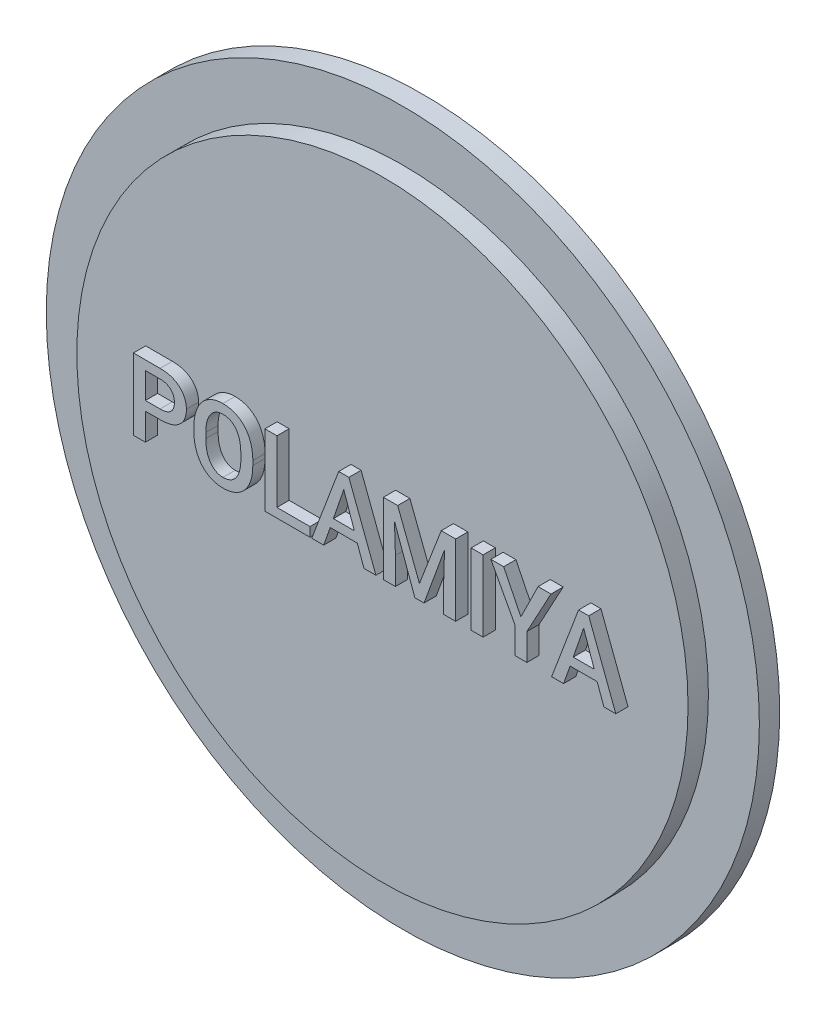
SolidWorks part; units mm, degrees
ref_plane "前视基准面" through (0, 0, 0) normal (0, 0, 1) x (1, 0, 0)
ref_plane "上视基准面" through (0, 0, 0) normal (0, 1, 0) x (1, 0, 0)
ref_plane "右视基准面" through (0, 0, 0) normal (1, 0, 0) x (0, 0, -1)
sketch "草图1" plane through (0, 0, 0) normal (0, 0, 1) x (1, 0, 0)
  circle A0 centre (0, 0) radius 17.5
  dimension "D1" = 35
extrude "凸台-拉伸1" add sketch "草图1" along normal blind 1
sketch "草图2" plane through (0, 0, 1) normal (0, 0, 1) x (1, 0, 0)
  circle A0 centre (0, 0) radius 15
  dimension "D1" = 30
extrude "凸台-拉伸2" add sketch "草图2" along normal blind 1
sketch "草图3" plane through (0, 0, 2) normal (0, 0, 1) x (1, 0, 0)
  line L0 (-14.9248, -1.5) -> (14.9248, -1.5) construction
  circle A0 centre (0, 0) radius 15 construction
  text T0 "<b>POLAMIYA</b>" font "Roboto" height 3.5
  dimension "D1" = 1.5
extrude "凸台-拉伸3" add sketch "草图3" along normal blind 0.6
